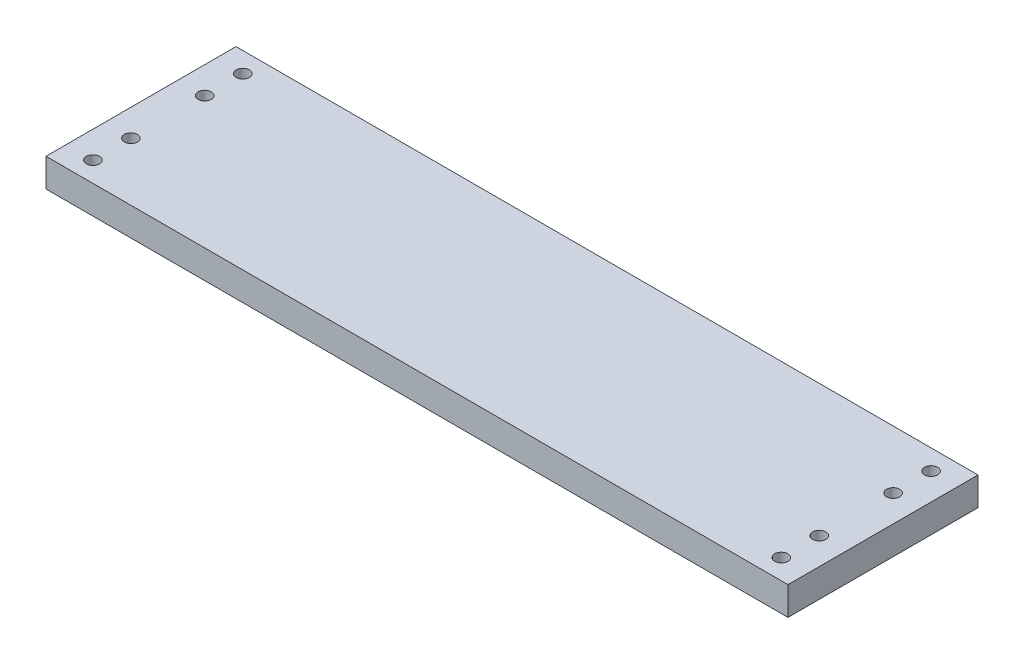
SolidWorks part; units mm, degrees
ref_plane "Front Plane" through (0, 0, 0) normal (0, 0, 1) x (1, 0, 0)
ref_plane "Top Plane" through (0, 0, 0) normal (0, 1, 0) x (1, 0, 0)
ref_plane "Right Plane" through (0, 0, 0) normal (1, 0, 0) x (0, 0, -1)
sketch "Sketch1" plane through (0, 0, 0) normal (0, 1, 0) x (1, 0, 0)
  line L1 (-83, 21.255) -> (83, 21.255)
  line L2 (-83, 21.255) -> (-83, -21.255)
  line L3 (-83, -21.255) -> (83, -21.255)
  line L4 (83, 21.255) -> (83, -21.255)
  line L5 (-83, 21.255) -> (83, -21.255) construction
  line L6 (-83, -21.255) -> (83, 21.255) construction
  point P0 (0, 0)
  dimension "2.25" = 42.51
  dimension "D2" = 166
extrude "Boss-Extrude1" add sketch "Sketch1" along normal blind 6.35 contours L2 L3 L4 L1
sketch "Sketch2" plane through (0, 6.35, 0) normal (0, 1, 0) x (1, 0, 0)
  line L0 (-77, 16.755) -> (0, 16.755)
  line L1 (0, 16.755) -> (77, 16.755)
  line L5 (77, 8.255) -> (0, 8.255)
  line L6 (0, 8.255) -> (-77, 8.255)
  line L7 (-77, 8.255) -> (-77, 16.755)
  line L10 (0, 0) -> (0, 8.255) construction
  line L11 (0, 16.755) -> (0, 8.255) construction
  line L12 (77, 16.755) -> (77, 8.255)
  dimension "D1" = 77
  dimension "D2" = 8.255
  dimension "D6" = 8.5
hole_wizard "#4 Clearance Hole1" positions "Sketch3" profile "Sketch5" hole size "#4" standard "ANSI Inch" end condition through all
sketch "Sketch3" plane through (0, 6.35, 0) normal (0, 1, 0) x (1, 0, 0)
  point P0 (-77, 8.255)
  point P2 (-77, 16.755)
  point P8 (77, 8.255)
  point P10 (77, 16.755)
sketch "Sketch5" plane through (-77, 6.35, -8.255) normal (1, 0, 0) x (0, 0, 1)
  line L0 (0, 0) -> (0, 6.35)
  line L1 (0, 6.35) -> (1.4732, 6.35)
  line L2 (1.4732, 6.35) -> (1.4732, 0)
  line L5 (1.4732, 0) -> (0, 0)
  line L11 (0, -6.35) -> (0, 107.95) construction
  dimension "Thru Hole Dia." = 2.9464
  dimension "Thru Hole Depth" = 6.35
sketch "Sketch6" plane through (0, 0, 0) normal (0, -1, 0) x (1, 0, 0)
  line L1 (-78.8331, -19.93) -> (-75.1669, -19.93)
  line L2 (-75.1669, -19.93) -> (-73.3338, -16.755)
  line L3 (-73.3338, -16.755) -> (-75.1669, -13.58)
  line L4 (-75.1669, -13.58) -> (-78.8331, -13.58)
  line L5 (-78.8331, -13.58) -> (-80.6662, -16.755)
  line L6 (-80.6662, -16.755) -> (-78.8331, -19.93)
  line L7 (-78.8331, -5.08) -> (-80.6662, -8.255)
  line L8 (-80.6662, -8.255) -> (-78.8331, -11.43)
  line L9 (-78.8331, -11.43) -> (-75.1669, -11.43)
  line L10 (-75.1669, -11.43) -> (-73.3338, -8.255)
  line L11 (-73.3338, -8.255) -> (-75.1669, -5.08)
  line L12 (-75.1669, -5.08) -> (-78.8331, -5.08)
  line L25 (78.8331, -11.43) -> (80.6662, -8.255)
  line L26 (80.6662, -8.255) -> (78.8331, -5.08)
  line L27 (78.8331, -5.08) -> (75.1669, -5.08)
  line L28 (75.1669, -5.08) -> (73.3338, -8.255)
  line L29 (73.3338, -8.255) -> (75.1669, -11.43)
  line L30 (75.1669, -11.43) -> (78.8331, -11.43)
  line L31 (78.8331, -19.93) -> (80.6662, -16.755)
  line L32 (80.6662, -16.755) -> (78.8331, -13.58)
  line L33 (78.8331, -13.58) -> (75.1669, -13.58)
  line L34 (75.1669, -13.58) -> (73.3338, -16.755)
  line L35 (73.3338, -16.755) -> (75.1669, -19.93)
  line L36 (75.1669, -19.93) -> (78.8331, -19.93)
  circle A0 centre (-77, -16.755) radius 3.175 construction
  circle A1 centre (-77, -8.255) radius 3.175 construction
  circle A4 centre (77, -8.255) radius 3.175 construction
  circle A5 centre (77, -16.755) radius 3.175 construction
  dimension "D1" = 6.35
hole_wizard "CSK for #4 Flat Head Socket Cap Screw1" positions "Sketch7" profile "Sketch8" countersink size "#4" standard "ANSI Inch" end condition through all
sketch "Sketch7" plane through (0, 0, 0) normal (0, -1, 0) x (-1, 0, 0)
  point P0 (77, 8.255)
  point P3 (77, 16.755)
  point P6 (-77, 8.255)
  point P9 (-77, 16.755)
sketch "Sketch8" plane through (-77, 0, -8.255) normal (1, 0, 0) x (0, 0, -1)
  line L0 (0, 0) -> (0, 6.35)
  line L1 (0, 6.35) -> (1.4732, 6.35)
  line L2 (1.4732, 6.35) -> (1.4732, 2.2808)
  line L3 (1.4732, 2.2808) -> (3.4558, 0)
  line L5 (3.4558, 0) -> (0, 0)
  line L6 (-1.4732, 2.2808) -> (-3.4558, 0) construction
  line L11 (0, -6.35) -> (0, 107.95) construction
  dimension "Thru Hole Dia." = 2.9464
  dimension "Thru Hole Depth" = 6.35
  dimension "Near C'Sink Dia." = 6.9117
  dimension "Near C'Sink Angle" = 82
mirror "Mirror1" about plane through (0, 0, 0) normal (0, 0, 1) of "CSK for #4 Flat Head Socket Cap Screw1"
